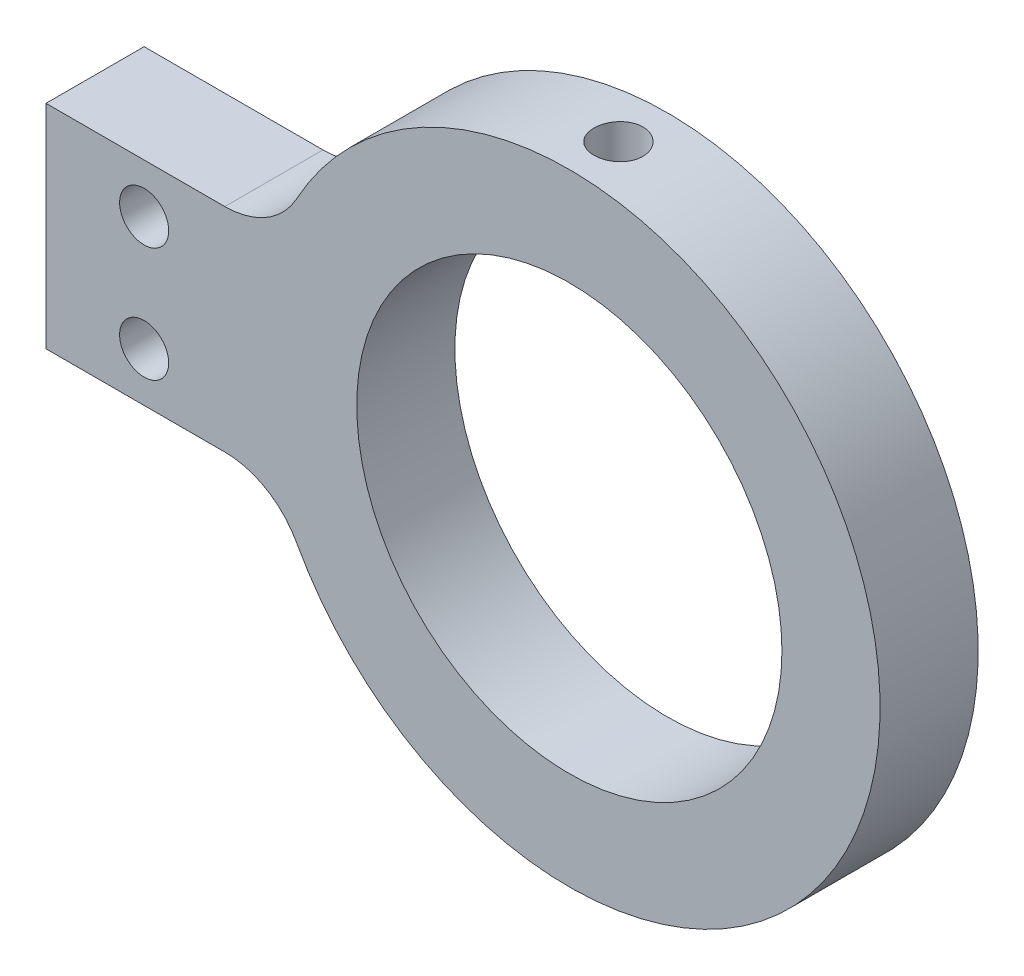
SolidWorks part; units mm, degrees
material "Brass"
ref_plane "Front Plane" through (0, 0, 0) normal (0, 0, 1) x (1, 0, 0)
ref_plane "Top Plane" through (0, 0, 0) normal (0, 1, 0) x (1, 0, 0)
ref_plane "Right Plane" through (0, 0, 0) normal (1, 0, 0) x (0, 0, -1)
sketch "Sketch1" plane through (0, 0, 0) normal (0, 0, 1) x (1, 0, 0)
  line L0 (0, 0) -> (-15715.7246, 0) construction
  line L1 (-21.0654, 6.5) -> (-32, 6.5)
  line L5 (-32, -6.5) -> (-32, 6.5)
  line L6 (-10.825, -6.5) -> (-32, 6.5) construction
  line L7 (-10.825, 6.5) -> (-32, -6.5) construction
  line L8 (-21.0654, -6.5) -> (-32, -6.5)
  arc A0 (-16.6768, -9.1042) -> (-16.6768, 9.1042) centre (0, 0) ccw
  circle A1 centre (0, 0) radius 13
  circle A2 centre (-26, 3.5) radius 1.5
  circle A3 centre (-26, -3.5) radius 1.5
  arc A4 (-21.0654, -6.5) -> (-16.6768, -9.1042) centre (-21.0654, -11.5) cw
  arc A5 (-21.0654, 6.5) -> (-16.6768, 9.1042) centre (-21.0654, 11.5) ccw
  point P4 (-21.4125, 0)
  point P16 (-32, 0)
  dimension "D1" = 38
  dimension "D2" = 26
  dimension "D4" = 32
  dimension "D5" = 3
  dimension "D8" = 5
  dimension "D3" = 13
  dimension "D6" = 6
  dimension "D7" = 3.5
extrude "Boss-Extrude1" add sketch "Sketch1" along normal mid plane 6
cosmetic thread "Cosmetic Thread1" parameters "D2"=4
cosmetic thread "Cosmetic Thread2" parameters "D2"=4
sketch "Sketch2" plane through (0, 0, 0) normal (0, 1, 0) x (1, 0, 0)
  circle A0 centre (0, 0) radius 1.5
  dimension "3" = 3
extrude "Cut-Extrude1" cut sketch "Sketch2" along normal up to next
